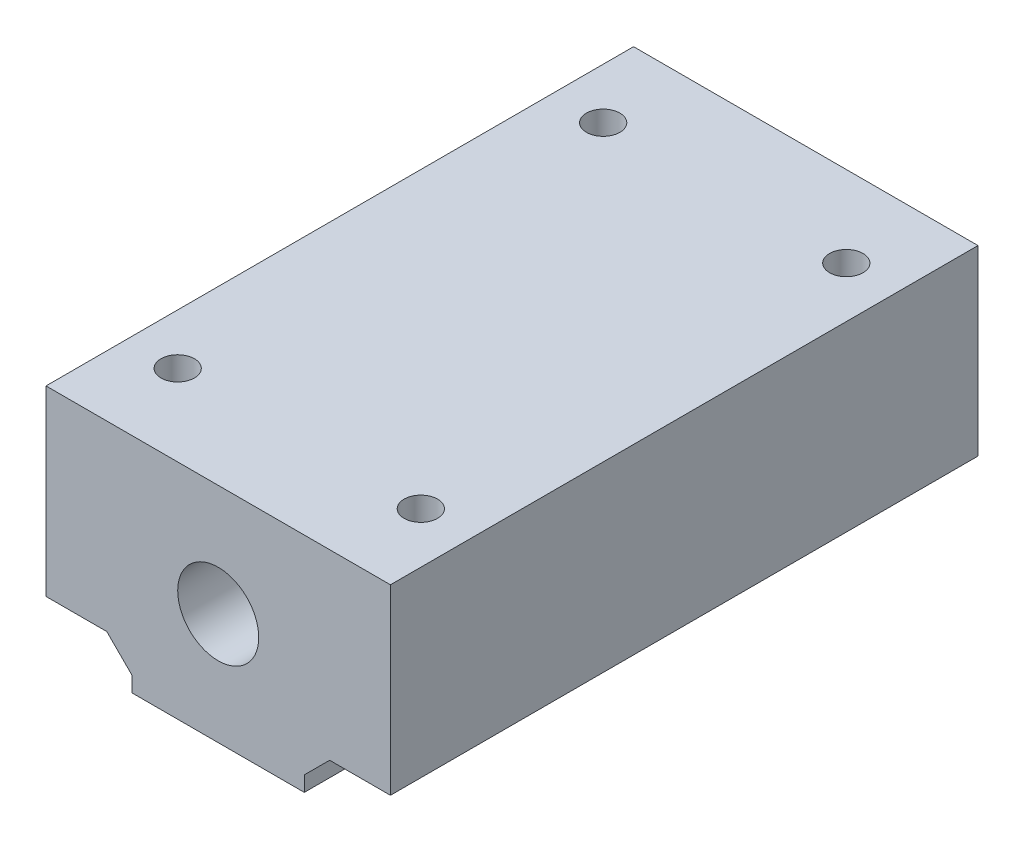
SolidWorks part; units mm, degrees
ref_plane "前视基准面" through (0, 0, 0) normal (0, 0, 1) x (1, 0, 0)
ref_plane "上视基准面" through (0, 0, 0) normal (0, 1, 0) x (1, 0, 0)
ref_plane "右视基准面" through (0, 0, 0) normal (1, 0, 0) x (0, 0, -1)
sketch "草图1" plane through (0, 0, 0) normal (0, 0, 1) x (1, 0, 0)
  line L0 (8.5, 0) -> (-8.5, 0)
  line L1 (-8.5, 0) -> (-8.5, 1.5)
  line L2 (-11, 4) -> (-17, 4)
  line L3 (-17, 4) -> (-17, 22)
  line L4 (-17, 22) -> (17, 22)
  line L5 (-8.5, 1.5) -> (-11, 4)
  line L6 (0, 0) -> (0, 22) construction
  line L7 (8.5, 1.5) -> (11, 4)
  line L8 (17, 4) -> (17, 22)
  line L9 (11, 4) -> (17, 4)
  line L10 (8.5, 0) -> (8.5, 1.5)
  circle A0 centre (0, 11) radius 4
  point P3 (-8.5, 4)
  point P16 (8.5, 4)
  dimension "D3" = 8
  dimension "D1" = 17
  dimension "D2" = 22
  dimension "D4" = 11
  dimension "D5" = 18
  dimension "D6" = 6
extrude "凸台-拉伸1" add sketch "草图1" along normal blind 58
hole_wizard "M4 螺纹孔1" positions "草图4" profile "草图3" tap size "M4" standard "Gb" end condition through all
sketch "草图4" plane through (0, 22, 0) normal (0, 1, 0) x (-1, 0, 0)
  line L1 (-17, 58) -> (-17, 0) construction
  line L3 (-17, 0) -> (17, 0) construction
  point P0 (12, 50)
  point P2 (-12, 50)
  point P4 (-12, 8)
  point P6 (12, 8)
  dimension "D1" = 24
  dimension "D2" = 42
  dimension "D3" = 5
  dimension "D4" = 8
sketch "草图3" plane through (-12, 22, 50) normal (1, 0, 0) x (0, 0, 1)
  line L0 (0, 0) -> (0, 22)
  line L1 (0, 22) -> (1.65, 22)
  line L2 (1.65, 22) -> (1.65, 0)
  line L5 (1.65, 0) -> (0, 0)
  line L11 (0, -6.35) -> (0, 107.95) construction
  dimension "通孔螺纹孔钻头直径" = 3.3
  dimension "通孔螺纹孔钻头深度" = 22
cosmetic thread "孔螺蚊线1" parameters "D2"=4
cosmetic thread "孔螺蚊线2" parameters "D2"=4
cosmetic thread "孔螺蚊线3" parameters "D2"=4
cosmetic thread "孔螺蚊线4" parameters "D2"=4
